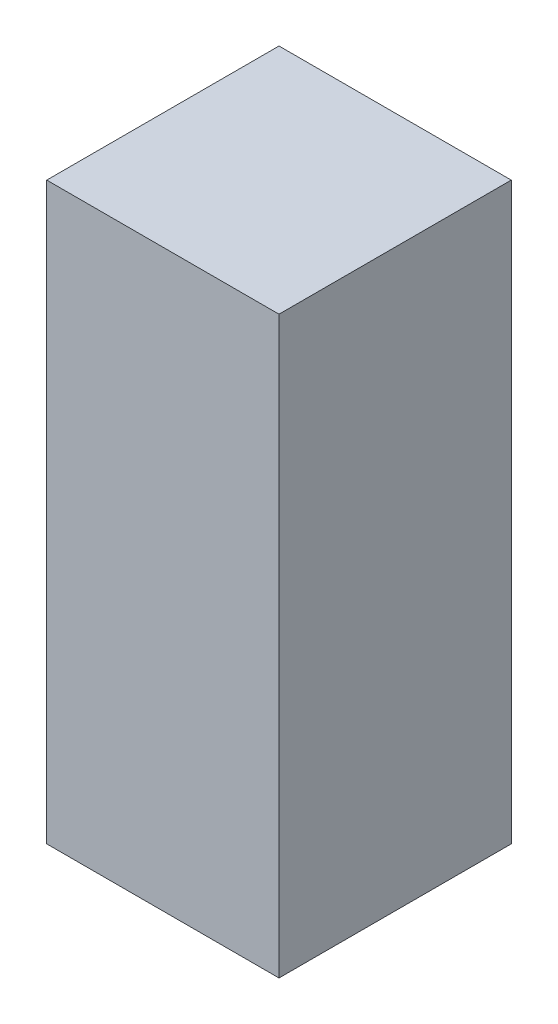
SolidWorks part; units mm, degrees
ref_plane "Front Plane" through (0, 0, 0) normal (0, 0, 1) x (1, 0, 0)
ref_plane "Top Plane" through (0, 0, 0) normal (0, 1, 0) x (1, 0, 0)
ref_plane "Right Plane" through (0, 0, 0) normal (1, 0, 0) x (0, 0, -1)
sketch "Sketch2" plane through (0, 0, 0) normal (1, 0, 0) x (0, 0, -1)
  line L1 (2.5654, 6.35) -> (-2.5654, 6.35)
  line L2 (2.5654, 6.35) -> (2.5654, -6.35)
  line L3 (2.5654, -6.35) -> (-2.5654, -6.35)
  line L4 (-2.5654, 6.35) -> (-2.5654, -6.35)
  line L5 (2.5654, 6.35) -> (-2.5654, -6.35) construction
  line L6 (2.5654, -6.35) -> (-2.5654, 6.35) construction
  point P0 (0, 0)
  dimension "D1" = 5.1308
  dimension "D2" = 12.7
extrude "Boss-Extrude1" add sketch "Sketch2" along normal blind 5.1308
